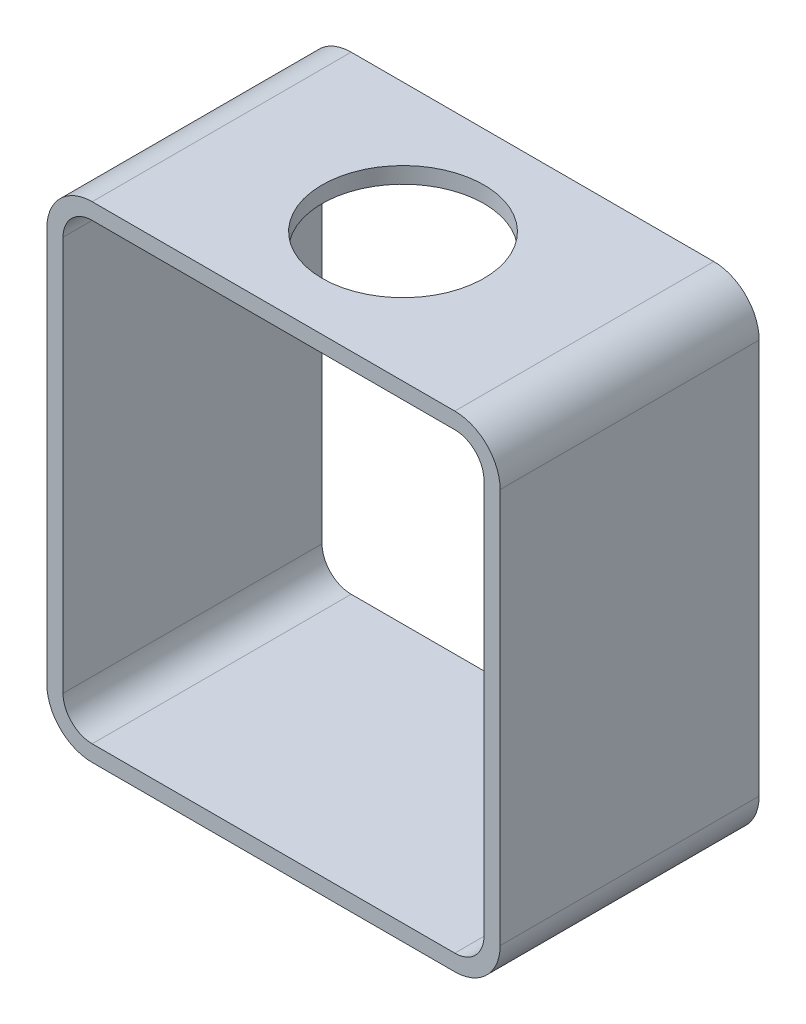
SolidWorks part; units mm, degrees
ref_plane "Спереди" through (0, 0, 0) normal (0, 0, 1) x (1, 0, 0)
ref_plane "Сверху" through (0, 0, 0) normal (0, 1, 0) x (1, 0, 0)
ref_plane "Справа" through (0, 0, 0) normal (1, 0, 0) x (0, 0, -1)
sketch "Эскиз1" plane through (0, 0, 0) normal (0, 0, 1) x (1, 0, 0)
  line L0 (0, 0) -> (28, 0)
  line L1 (28, 0) -> (28, 30)
  line L2 (28, 30) -> (0, 30)
  line L3 (0, 30) -> (0, 0)
  line L4 (1, 29) -> (1, 1)
  line L5 (1, 1) -> (27, 1)
  line L6 (27, 1) -> (27, 29)
  line L7 (27, 29) -> (1, 29)
  dimension "D1" = 1
extrude "Бобышка-Вытянуть1" add sketch "Эскиз1" along normal blind 16
fillet "Скругление1" radius 1.8 4 edges at (27, 1, 8) (1, 1, 8) (1, 29, 8) (27, 29, 8)
fillet "Скругление2" radius 2.8 4 edges at (28, 0, 8) (0, 0, 8) (0, 30, 8) (28, 30, 8)
sketch "Эскиз2" plane through (0, 30, 0) normal (0, 1, 0) x (1, 0, 0)
  circle A0 centre (14, -8) radius 5
extrude "Вырез-Вытянуть1" cut sketch "Эскиз2" against normal blind 16
